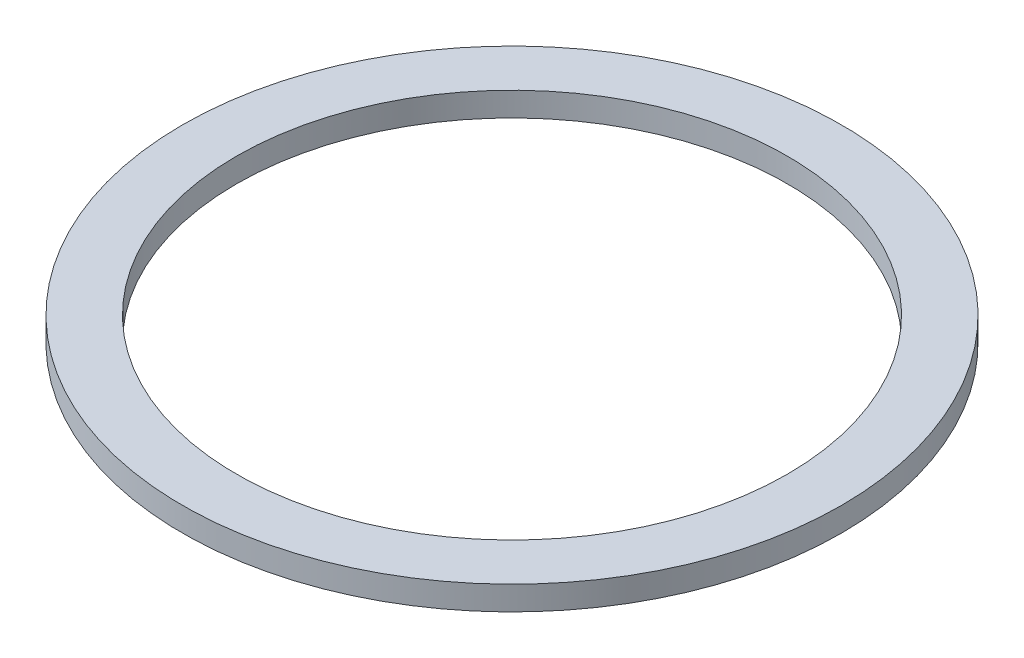
SolidWorks part; units mm, degrees
ref_plane "Front Plane" through (0, 0, 0) normal (0, 0, 1) x (1, 0, 0)
ref_plane "Top Plane" through (0, 0, 0) normal (0, 1, 0) x (1, 0, 0)
ref_plane "Right Plane" through (0, 0, 0) normal (1, 0, 0) x (0, 0, -1)
sketch "Sketch1" plane through (0, 0, 0) normal (0, 0, 1) x (1, 0, 0)
  line L0 (0, -200000) -> (0, 218797.9879) construction
  line L5 (0, -200000) -> (0, 218797.9879) construction
  line L6 (174.1012, 198.7837) -> (174.1012, 186.0837)
  line L7 (145.5262, 198.7837) -> (174.1012, 198.7837)
  line L8 (174.1012, 186.0837) -> (145.5262, 186.0837)
  line L9 (145.5262, 186.0837) -> (145.5262, 198.7837)
revolve "Revolve1" add sketch "Sketch1" angle 360 about L5
